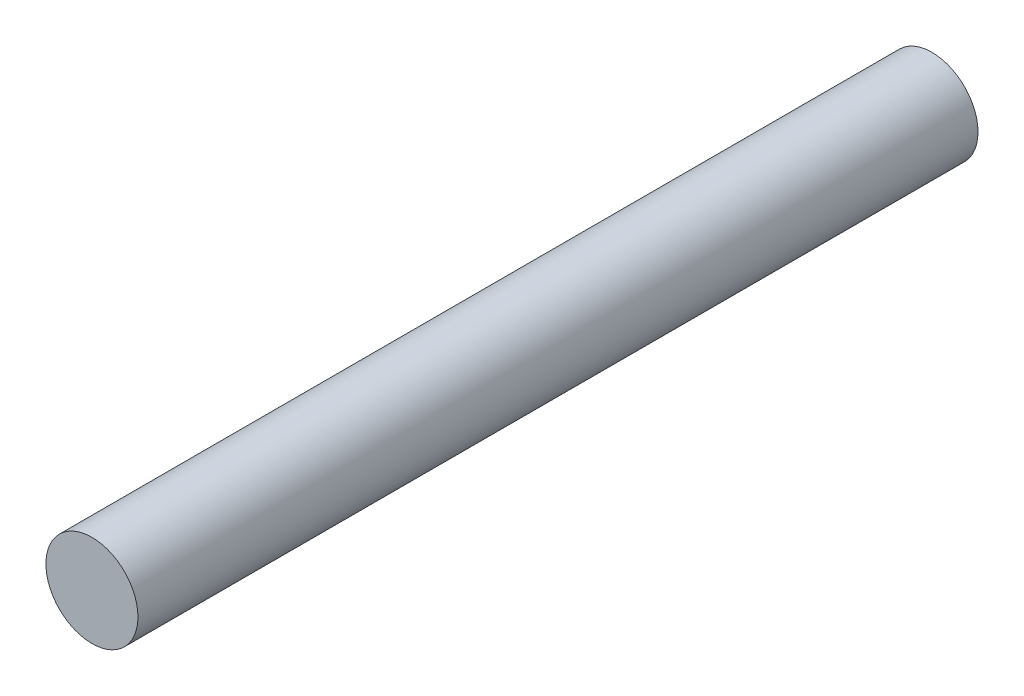
SolidWorks part; units mm, degrees
ref_plane "前视基准面" through (0, 0, 0) normal (0, 0, 1) x (1, 0, 0)
ref_plane "上视基准面" through (0, 0, 0) normal (0, 1, 0) x (1, 0, 0)
ref_plane "右视基准面" through (0, 0, 0) normal (1, 0, 0) x (0, 0, -1)
sketch "草图1" plane through (0, 0, 0) normal (0, 0, 1) x (1, 0, 0)
  circle A0 centre (0, 0) radius 0.8
  dimension "D1" = 1.6
extrude "凸台-拉伸1" add sketch "草图1" along normal blind 14.6
